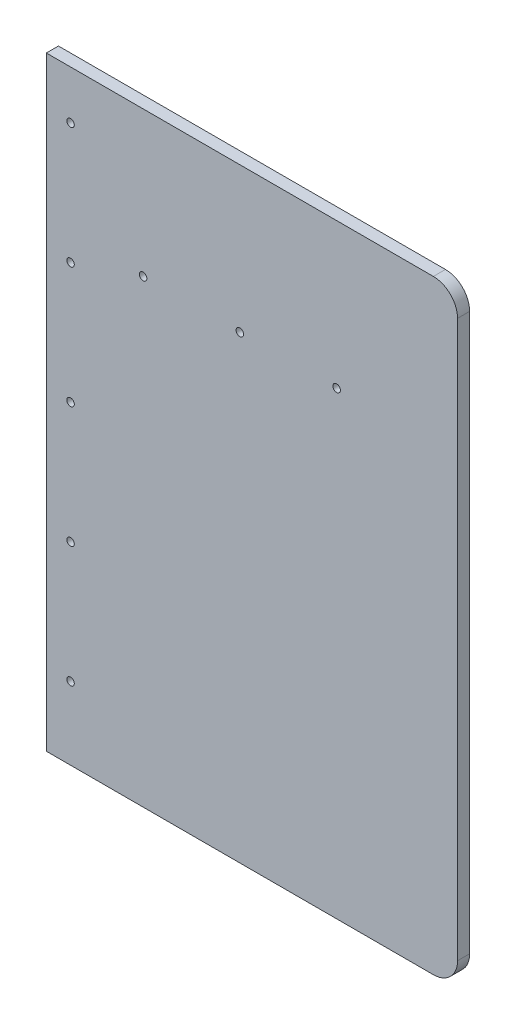
SolidWorks part; units mm, degrees
ref_plane "Alzado" through (0, 0, 0) normal (0, 0, 1) x (1, 0, 0)
ref_plane "Planta" through (0, 0, 0) normal (0, 1, 0) x (1, 0, 0)
ref_plane "Vista lateral" through (0, 0, 0) normal (1, 0, 0) x (0, 0, -1)
sketch "Croquis1" plane through (0, 0, 0) normal (0, 0, 1) x (1, 0, 0)
  line L0 (-75, 125) -> (-75, -125) construction
  line L1 (75, 125) -> (-85, 125)
  line L2 (85, 115) -> (85, -115)
  line L3 (75, -125) -> (-85, -125)
  line L4 (-85, 125) -> (-85, -125)
  line L5 (85, 125) -> (-85, -125) construction
  line L6 (85, -125) -> (-85, 125) construction
  line L7 (85, 65) -> (-85, 65) construction
  line L8 (-75, 75) -> (-75, -175) construction
  line L9 (-75, 25) -> (-75, -225) construction
  line L10 (-75, -25) -> (-75, -275) construction
  line L11 (-75, -75) -> (-75, -325) construction
  circle A0 centre (35, 65) radius 1.55
  circle A1 centre (-75, 105) radius 1.55
  circle A2 centre (-75, 55) radius 1.55
  circle A3 centre (-75, 5) radius 1.55
  circle A4 centre (-75, -45) radius 1.55
  circle A5 centre (-75, -95) radius 1.55
  circle A6 centre (-5, 65) radius 1.55
  circle A7 centre (-45, 65) radius 1.55
  arc A8 (85, 115) -> (75, 125) centre (75, 115) ccw
  arc A9 (75, -125) -> (85, -115) centre (75, -115) ccw
  point P0 (0, 0)
  dimension "D7" = 3.1
  dimension "D8" = 3.1
  dimension "D11" = 10
  dimension "D1" = 250
  dimension "D2" = 10
  dimension "D3" = 170
  dimension "D4" = 60
  dimension "D5" = 20
  dimension "D6" = 50
  dimension "D9" = 5
  dimension "D10" = 3
extrude "Saliente-Extruir1" add sketch "Croquis1" along normal blind 5
